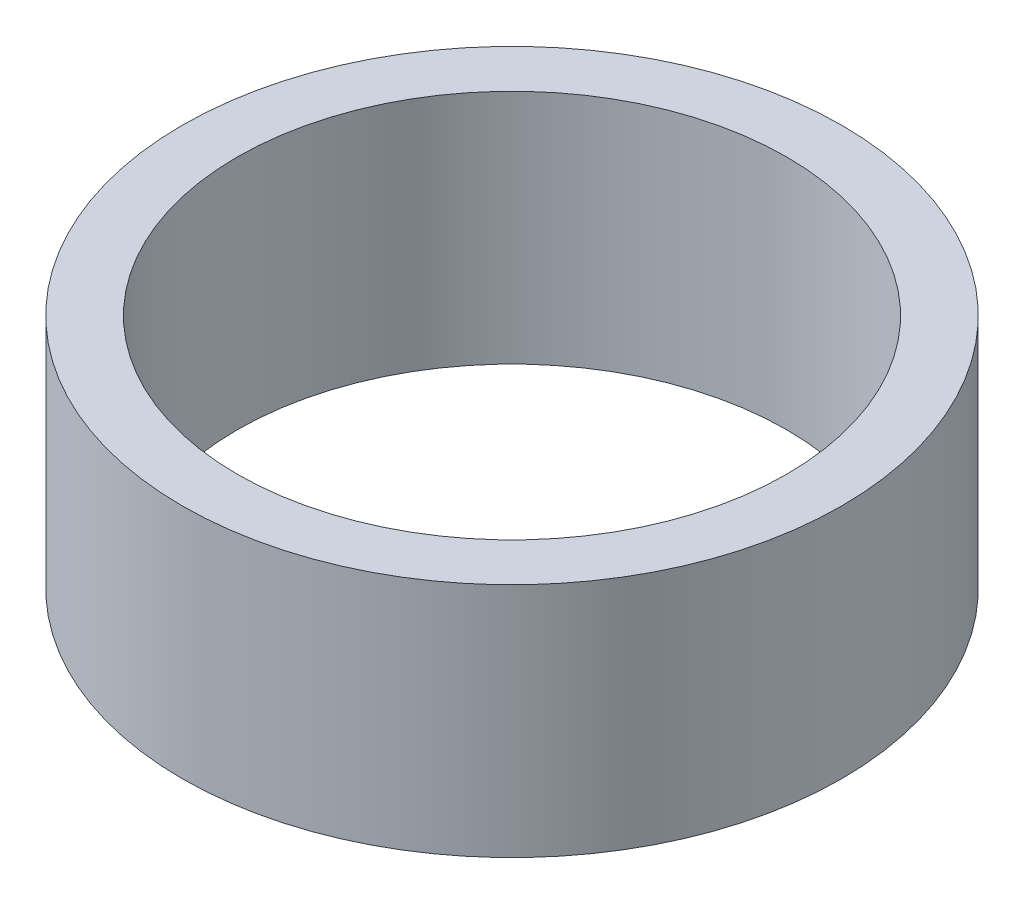
SolidWorks part; units mm, degrees
material "Alumina"
ref_plane "Front Plane" through (0, 0, 0) normal (0, 0, 1) x (1, 0, 0)
ref_plane "Top Plane" through (0, 0, 0) normal (0, 1, 0) x (1, 0, 0)
ref_plane "Right Plane" through (0, 0, 0) normal (1, 0, 0) x (0, 0, -1)
sketch "Sketch1" plane through (0, 0, 0) normal (0, 1, 0) x (1, 0, 0)
  circle A0 centre (0, 0) radius 60
  dimension "D1" = 120
extrude "Boss-Extrude1" add sketch "Sketch1" along normal blind 43
sketch "Sketch2" plane through (0, 0, 0) normal (0, -1, 0) x (1, 0, 0)
  circle A0 centre (0, 0) radius 50
  dimension "D1" = 100
extrude "Cut-Extrude1" cut sketch "Sketch2" against normal up to surface (43 mm away) up to face at (0, 43, 60)
